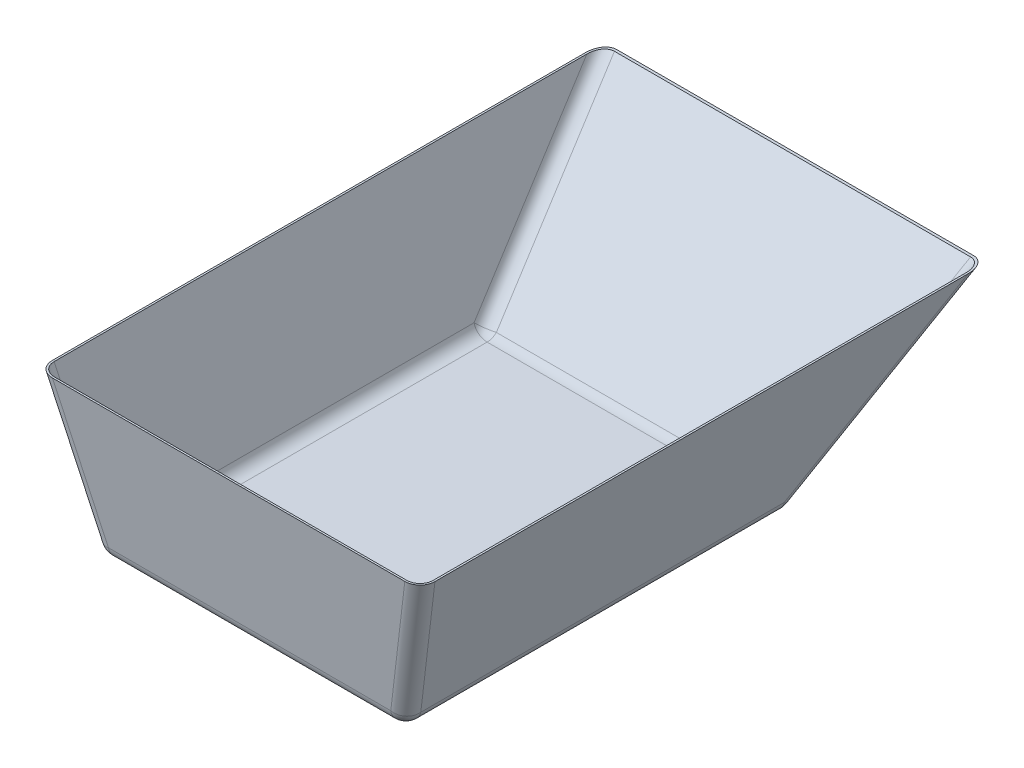
SolidWorks part; units mm, degrees
ref_plane "前基準面" through (0, 0, 0) normal (0, 0, 1) x (1, 0, 0)
ref_plane "上基準面" through (0, 0, 0) normal (0, 1, 0) x (1, 0, 0)
ref_plane "右基準面" through (0, 0, 0) normal (1, 0, 0) x (0, 0, -1)
sketch "草圖1" plane through (0, 0, 0) normal (0, 0, 1) x (1, 0, 0)
  line L1 (-125, 50) -> (125, 50)
  line L2 (-125, 50) -> (-125, -50)
  line L3 (-125, -50) -> (125, -50)
  line L4 (125, 50) -> (125, -50)
  dimension "D1" = 100
  dimension "D2" = 50
  dimension "D3" = 125
  dimension "D4" = 250
extrude "填料-伸長1" add sketch "草圖1" along normal blind 370
sketch "草圖2" plane through (0, 0, 370) normal (0, 0, 1) x (1, 0, 0)
  line L0 (0, 50) -> (0, -50) construction
  line L1 (125, 50) -> (-125, 50) construction
  line L2 (-125, -50) -> (125, -50) construction
  line L3 (-125, 50) -> (-100, -50)
  line L4 (-100, -50) -> (-125, -50)
  line L5 (-125, -50) -> (-125, 50)
  line L6 (125, 50) -> (125, -50)
  line L7 (125, -50) -> (100, -50)
  line L8 (100, -50) -> (125, 50)
  dimension "D1" = 25
  dimension "D2" = 25
extrude "除料-伸長1" cut sketch "草圖2" against normal blind 370
ref_plane "平面4" through (-125, 50, 370) normal (-1, 0, 0) x (0, 0, 1)
sketch "草圖7" plane through (-125, 50, 370) normal (-1, 0, 0) x (0, 0, 1)
  line L0 (0, 0) -> (-15, -100)
  line L1 (-370, -100) -> (0, -100) construction
  line L2 (-15, -100) -> (0, -100)
  line L3 (0, -100) -> (0, 0)
  line L4 (-370, 0) -> (-265, -100)
  line L5 (-265, -100) -> (-370, -100)
  line L6 (-370, -100) -> (-370, 0)
  dimension "D1" = 250
  dimension "D2" = 105
extrude "除料-伸長3" cut sketch "草圖7" against normal through all
fillet "圓角1" radius 10 8 edges at (-100, -50, 230) (0, -50, 355) (100, -50, 230) (0, -50, 105) (112.5, 0, 52.5) (-112.5, 0, 52.5) (-112.5, 0, 362.5) (112.5, 0, 362.5)
shell "薄殼2" thickness 1.2
